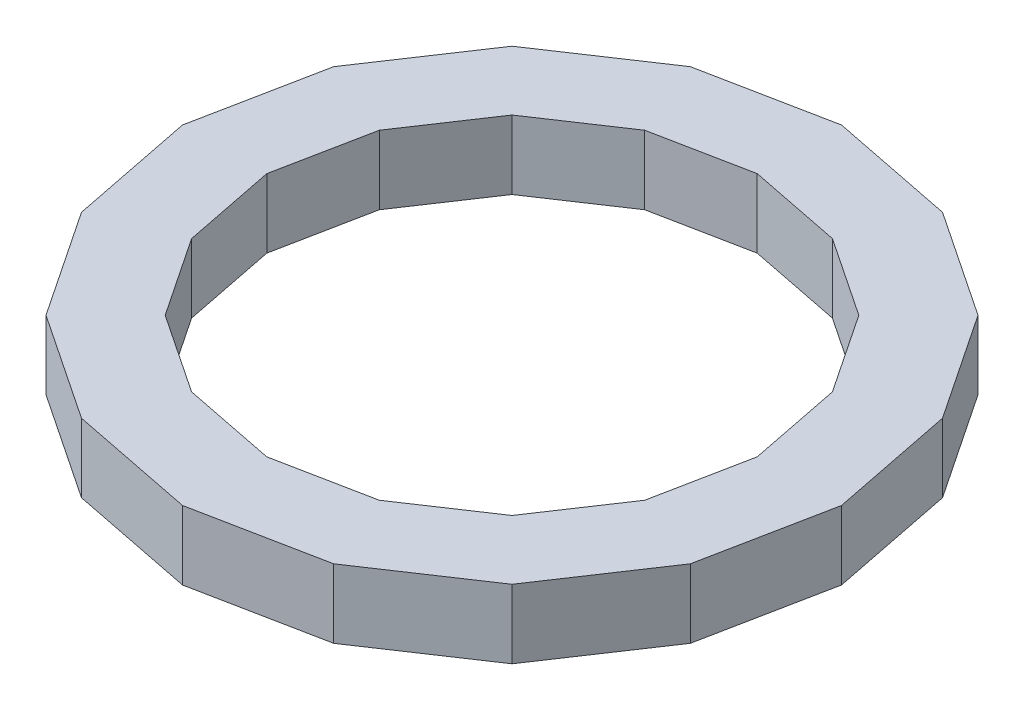
SolidWorks part; units mm, degrees
ref_plane "Front Plane" through (0, 0, 0) normal (0, 0, 1) x (1, 0, 0)
ref_plane "Top Plane" through (0, 0, 0) normal (0, 1, 0) x (1, 0, 0)
ref_plane "Right Plane" through (0, 0, 0) normal (1, 0, 0) x (0, 0, -1)
sketch "Sketch1" plane through (0, 0, 0) normal (0, 1, 0) x (1, 0, 0)
  line L1 (67.8294, 0) -> (62.6662, 25.9572)
  line L2 (62.6662, 25.9572) -> (47.9626, 47.9626)
  line L3 (47.9626, 47.9626) -> (25.9572, 62.6662)
  line L4 (25.9572, 62.6662) -> (0, 67.8294)
  line L5 (0, 67.8294) -> (-25.9572, 62.6662)
  line L6 (-25.9572, 62.6662) -> (-47.9626, 47.9626)
  line L7 (-47.9626, 47.9626) -> (-62.6662, 25.9572)
  line L8 (-62.6662, 25.9572) -> (-67.8294, 0)
  line L9 (-67.8294, 0) -> (-62.6662, -25.9572)
  line L10 (-62.6662, -25.9572) -> (-47.9626, -47.9626)
  line L11 (-47.9626, -47.9626) -> (-25.9572, -62.6662)
  line L12 (-25.9572, -62.6662) -> (0, -67.8294)
  line L13 (0, -67.8294) -> (25.9572, -62.6662)
  line L14 (25.9572, -62.6662) -> (47.9626, -47.9626)
  line L15 (47.9626, -47.9626) -> (62.6662, -25.9572)
  line L16 (62.6662, -25.9572) -> (67.8294, 0)
  line L17 (91.1373, 0) -> (84.1999, 34.8767)
  line L18 (84.1999, 34.8767) -> (64.4438, 64.4438)
  line L19 (64.4438, 64.4438) -> (34.8767, 84.1999)
  line L20 (34.8767, 84.1999) -> (0, 91.1373)
  line L21 (0, 91.1373) -> (-34.8767, 84.1999)
  line L22 (-34.8767, 84.1999) -> (-64.4438, 64.4438)
  line L23 (-64.4438, 64.4438) -> (-84.1999, 34.8767)
  line L24 (-84.1999, 34.8767) -> (-91.1373, 0)
  line L25 (-91.1373, 0) -> (-84.1999, -34.8767)
  line L26 (-84.1999, -34.8767) -> (-64.4438, -64.4438)
  line L27 (-64.4438, -64.4438) -> (-34.8767, -84.1999)
  line L28 (-34.8767, -84.1999) -> (0, -91.1373)
  line L29 (0, -91.1373) -> (34.8767, -84.1999)
  line L30 (34.8767, -84.1999) -> (64.4438, -64.4438)
  line L31 (64.4438, -64.4438) -> (84.1999, -34.8767)
  line L32 (84.1999, -34.8767) -> (91.1373, 0)
  circle A1 centre (0, 0) radius 66.5261 construction
  circle A2 centre (0, 0) radius 89.3861 construction
  dimension "D1" = 22.86
  dimension "D2" = 35.56
extrude "Boss-Extrude1" add sketch "Sketch1" along normal blind 19.05
